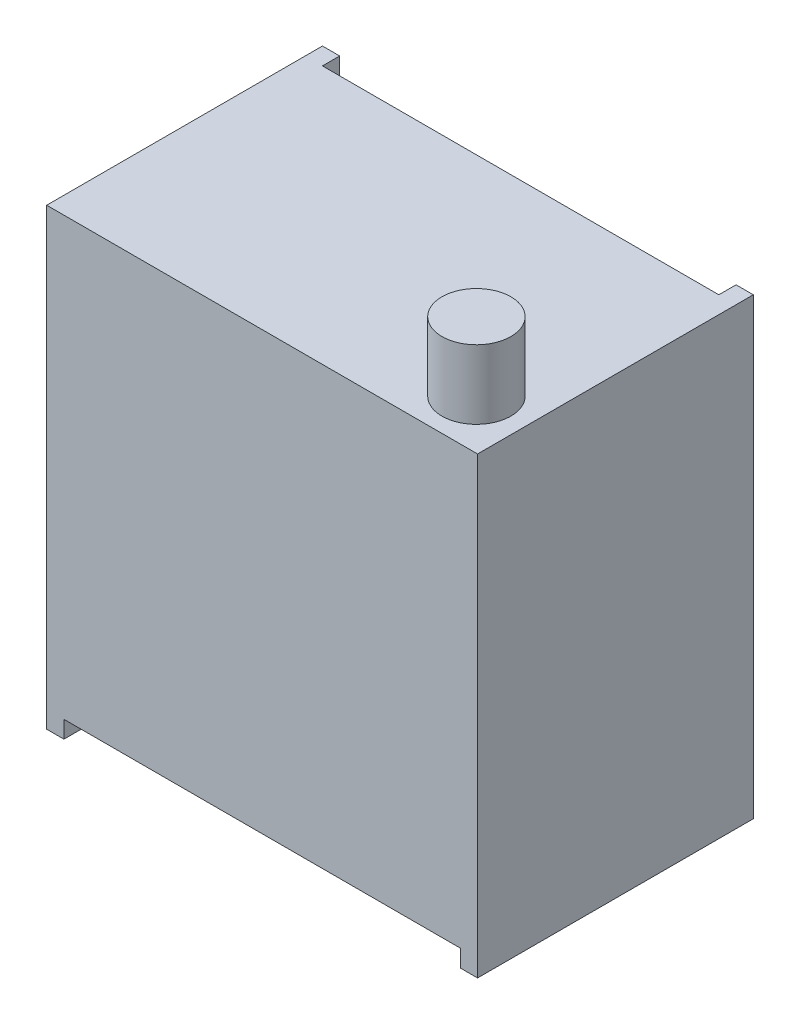
SolidWorks part; units mm, degrees
ref_plane "FRONT" through (0, 0, 0) normal (0, 0, 1) x (1, 0, 0)
ref_plane "TOP" through (0, 0, 0) normal (0, 1, 0) x (1, 0, 0)
ref_plane "RIGHT" through (0, 0, 0) normal (1, 0, 0) x (0, 0, -1)
sketch "Sketch1" plane through (0, 0, 0) normal (0, 0, 1) x (1, 0, 0)
  line L0 (0, 0) -> (0, 32.3262) construction
  line L1 (4.3815, 0) -> (4.7625, 0)
  line L2 (-4.7625, 10.033) -> (4.7625, 10.033)
  line L3 (-4.7625, 10.033) -> (-4.7625, 0)
  line L4 (-4.7625, 0) -> (-4.3815, 0)
  line L5 (4.7625, 10.033) -> (4.7625, 0)
  line L7 (4.3815, 0) -> (4.3815, 0.381)
  line L8 (4.3815, 0.381) -> (-4.3815, 0.381)
  line L9 (-4.3815, 0) -> (-4.3815, 0.381)
  dimension "D1" = 0.381
  dimension "D2" = 0.381
  dimension "D3" = 9.525
  dimension "D4" = 10.033
extrude "Base-Extrude" add sketch "Sketch1" against normal blind 6.096
sketch "Sketch2" plane through (0, 10.033, 0) normal (0, 1, 0) x (-1, 0, 0)
  line L0 (-4.7625, -6.096) -> (4.7625, -6.096) construction
  line L1 (4.3815, -6.096) -> (-4.3815, -6.096)
  line L2 (4.3815, -6.096) -> (4.3815, -5.715)
  line L3 (4.3815, -5.715) -> (-4.3815, -5.715)
  line L4 (-4.3815, -6.096) -> (-4.3815, -5.715)
  line L5 (-4.7625, -6.096) -> (-4.7625, 0) construction
  line L6 (4.7625, -6.096) -> (4.7625, 0) construction
  dimension "D1" = 0.381
  dimension "D2" = 0.381
  dimension "D3" = 0.381
extrude "Cut-Extrude1" cut sketch "Sketch2" against normal through all
sketch "Sketch3" plane through (0, 10.033, 0) normal (0, 1, 0) x (-1, 0, 0)
  line L0 (-4.7625, 0) -> (4.7625, 0) construction
  line L1 (-4.7625, -6.096) -> (-4.7625, 0) construction
  circle A0 centre (-3.6449, -1.0922) radius 0.762
  dimension "D1" = 1.0922
  dimension "D2" = 1.1176
  dimension "D3" = 1.524
extrude "screw" add sketch "Sketch3" along normal blind 1.524
sketch "Sketch4" plane through (0, 0.381, 0) normal (0, -1, 0) x (1, 0, 0)
  line L0 (-5.0397, -4.191) -> (5.1143, -4.191) construction
  line L1 (-4.7625, -6.096) -> (-4.3815, -6.096) construction
  circle A0 centre (-2.54, -4.191) radius 0.254
  circle A1 centre (0, -4.191) radius 0.254
  circle A2 centre (2.54, -4.191) radius 0.254
  dimension "D1" = 0.508
  dimension "D3" = 2.54
  dimension "D4" = 2.54
  dimension "D2" = 1.905
extrude "Pins" add sketch "Sketch4" along normal blind 1.524
